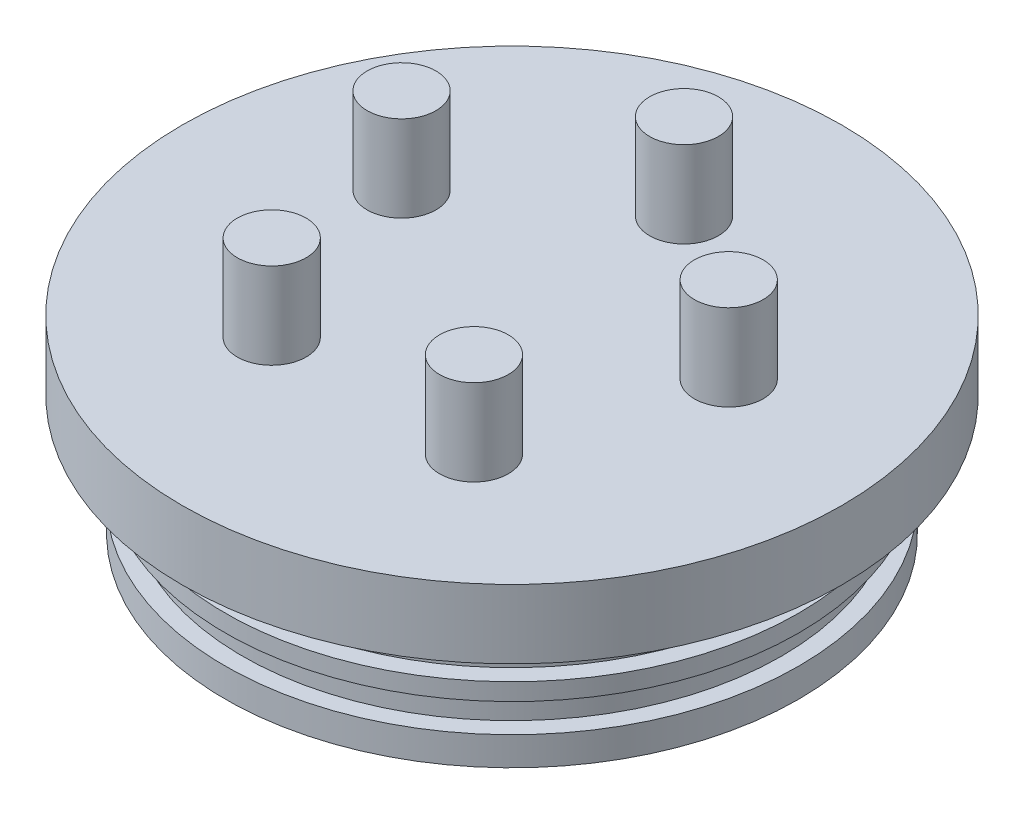
SolidWorks part; units mm, degrees
ref_plane "Plan de face" through (0, 0, 0) normal (0, 0, 1) x (1, 0, 0)
ref_plane "Plan de dessus" through (0, 0, 0) normal (0, 1, 0) x (1, 0, 0)
ref_plane "Plan de droite" through (0, 0, 0) normal (1, 0, 0) x (0, 0, -1)
sketch "Esquisse1" plane through (0, 0, 0) normal (0, 0, 1) x (1, 0, 0)
  line L0 (0, 0) -> (45, 0)
  line L1 (45, 0) -> (45, -27)
  line L2 (45, -27) -> (50, -27)
  line L3 (50, -27) -> (50, -22)
  line L4 (50, -6) -> (57.5, -6)
  line L5 (57.5, -6) -> (57.5, 6)
  line L6 (57.5, 6) -> (0, 6)
  line L7 (0, 6) -> (0, 0) construction
  line L8 (50, -22) -> (47, -22)
  line L9 (47, -22) -> (47, -17)
  line L10 (47, -17) -> (50, -17)
  line L11 (50, -14) -> (47, -14)
  line L12 (47, -14) -> (47, -9)
  line L13 (47, -9) -> (50, -9)
  line L14 (50, -9) -> (50, -6)
  line L15 (50, -17) -> (50, -14)
  line L16 (0, 0) -> (0, 6)
  dimension "D1" = 100
  dimension "D2" = 5
  dimension "D3" = 21
  dimension "D4" = 115
  dimension "D5" = 5
  dimension "D6" = 5
  dimension "D7" = 5
  dimension "D8" = 3
  dimension "D9" = 3
  dimension "D10" = 6
  dimension "D11" = 12
revolve "Révolution1" add sketch "Esquisse1" angle 360 about L16
sketch "Esquisse2" plane through (0, 6, 0) normal (0, 1, 0) x (1, 0, 0)
  circle A0 centre (0, 30) radius 6
  circle A1 centre (28.5317, 9.2705) radius 6
  circle A2 centre (17.6336, -24.2705) radius 6
  circle A3 centre (-17.6336, -24.2705) radius 6
  circle A4 centre (-28.5317, 9.2705) radius 6
  point P13 (0, 0)
  dimension "D1" = 12
  dimension "D2" = 30
  dimension "D3" = 5
extrude "Boss.-Extru.1" add sketch "Esquisse2" along normal blind 15
